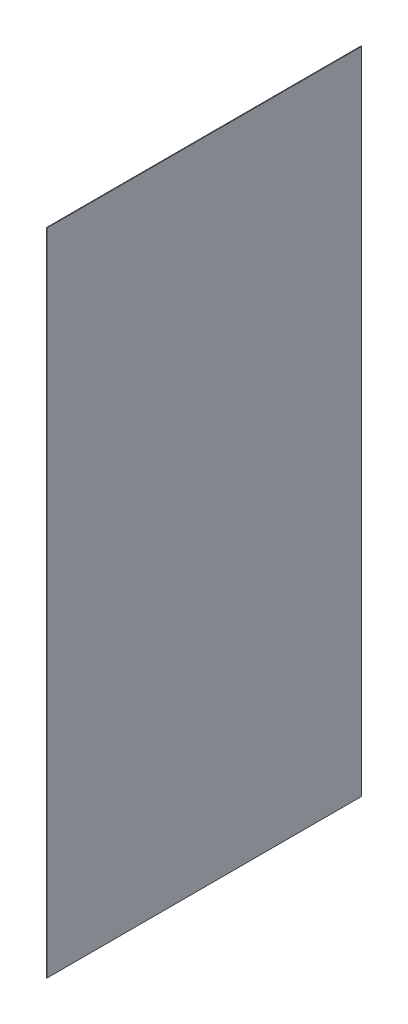
SolidWorks part; units mm, degrees
ref_plane "Front Plane" through (0, 0, 0) normal (0, 0, 1) x (1, 0, 0)
ref_plane "Top Plane" through (0, 0, 0) normal (0, 1, 0) x (1, 0, 0)
ref_plane "Right Plane" through (0, 0, 0) normal (1, 0, 0) x (0, 0, -1)
sketch "Sketch1" plane through (0, 0, 0) normal (1, 0, 0) x (0, 0, -1)
  line L1 (-32.8621, 3504.1394) -> (1687.9879, 3504.1394)
  line L2 (-32.8621, 3504.1394) -> (-32.8621, -51.8606)
  line L3 (-32.8621, -51.8606) -> (1687.9879, -51.8606)
  line L4 (1687.9879, 3504.1394) -> (1687.9879, -51.8606)
  dimension "D1" = 3556
  dimension "D2" = 1720.85
extrude "Boss-Extrude1" add sketch "Sketch1" along normal blind 3.175
